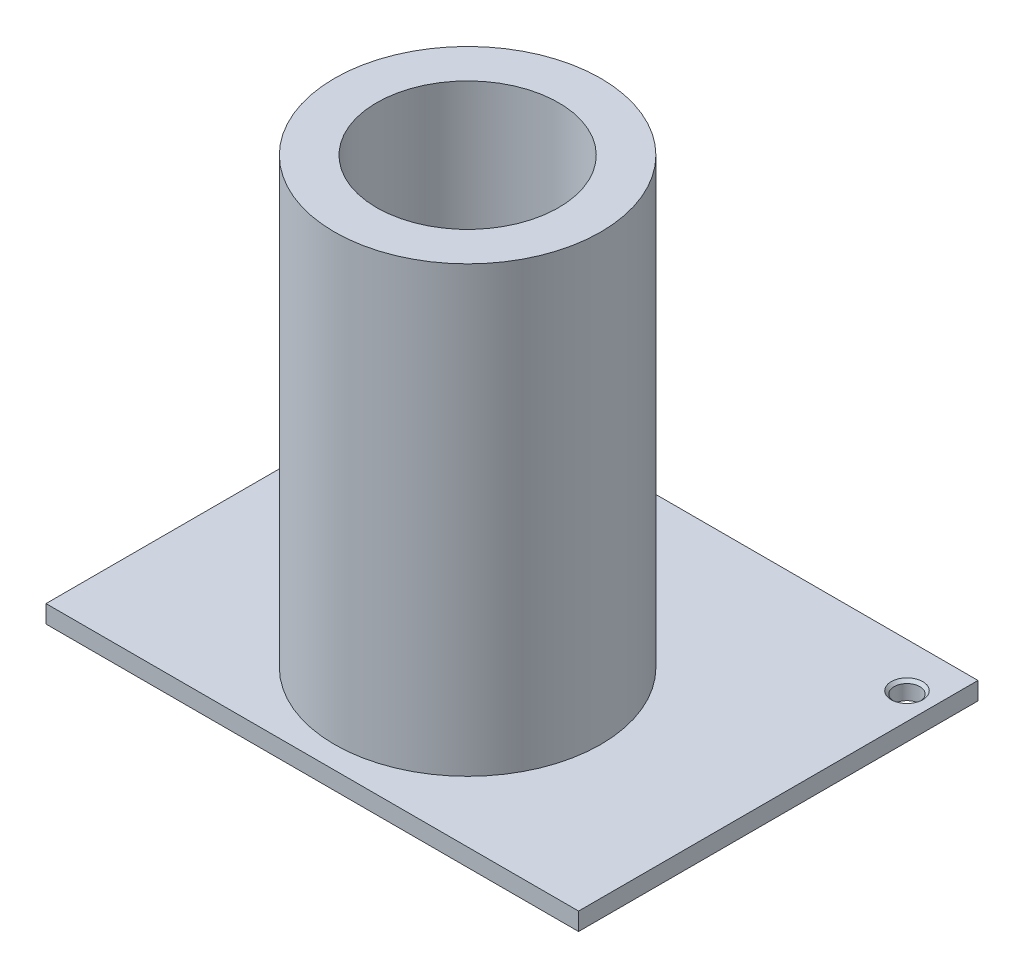
SolidWorks part; units mm, degrees
ref_plane "前视基准面" through (0, 0, 0) normal (0, 0, 1) x (1, 0, 0)
ref_plane "上视基准面" through (0, 0, 0) normal (0, 1, 0) x (1, 0, 0)
ref_plane "右视基准面" through (0, 0, 0) normal (1, 0, 0) x (0, 0, -1)
other "Configuration Table"
sketch "草图1" plane through (0, 0, 0) normal (0, 1, 0) x (1, 0, 0)
  line L0 (-30, 0) -> (-30, 30) construction
  line L2 (0, 0) -> (0, 30)
  line L3 (0, 30) -> (-60, 30)
  line L4 (-60, 0) -> (-60, 30)
  line L5 (-60, 30) -> (-57, 30)
  line L6 (-60, 0) -> (-60, -15)
  line L7 (-60, -15) -> (0, -15)
  line L8 (0, -15) -> (0, 0)
  dimension "D3" = 3
  dimension "D4" = 15
  dimension "D1" = 60
  dimension "D2" = 30
extrude "凸台-拉伸1" add sketch "草图1" along normal blind 2
sketch "草图2" plane through (0, 2, 0) normal (0, 1, 0) x (1, 0, 0)
  line L0 (-60, 30) -> (-57, 30) construction
  line L1 (0, 30) -> (-60, 30) construction
  line L2 (-57, 30) -> (-57, 25) construction
  line L3 (-30, 30) -> (-30, 0) construction
  circle A0 centre (-57, 25) radius 1.75
  circle A1 centre (-3, 25) radius 1.75
  point P6 (-57, 25)
  point P11 (-3, 25)
  point P18 (-57, 25)
  dimension "D1" = 3
  dimension "D2" = 5
hole_wizard "M3.5 螺纹孔1" positions "草图2" profile "草图3" tap size "M3.5" standard "GB"
sketch "草图3" plane through (-57, 2, -25) normal (1, 0, 0) x (0, 0, 1)
  line L0 (0, 0) -> (0, 9.6712)
  line L1 (0, 9.6712) -> (1.45, 8.8)
  line L2 (1.45, 8.8) -> (1.45, 0.325)
  line L3 (1.45, 0.325) -> (1.775, 0)
  line L5 (1.775, 0) -> (0, 0)
  line L6 (-1.45, 0.325) -> (-1.775, 0) construction
  line L10 (0, 9.6712) -> (-1.45, 8.8) construction
  line L11 (0, -6.35) -> (0, 107.95) construction
  dimension "螺纹孔钻头直径" = 2.9
  dimension "螺纹孔钻头深度" = 8.8
  dimension "近端锥形沉头孔直径" = 3.55
  dimension "近端锥形沉头孔角度" = 90
  dimension "导头角度" = 118
cosmetic thread "孔螺蚊线1" parameters "D1"=7, "D2"=3.5
cosmetic thread "孔螺蚊线2" parameters "D1"=7, "D2"=3.5
sketch "草图4" plane through (0, 2, 0) normal (0, 1, 0) x (1, 0, 0)
  line L0 (-60, -15) -> (-60, 2.5) construction
  line L1 (-60, -15) -> (-60, 30) construction
  line L2 (-60, 2.5) -> (0, 2.5) construction
  line L3 (0, -15) -> (0, 30) construction
  circle A0 centre (-30, 2.5) radius 10.25
  circle A1 centre (-30, 2.5) radius 15
  dimension "D1" = 17.5
extrude "凸台-拉伸2" add sketch "草图4" along normal blind 50
